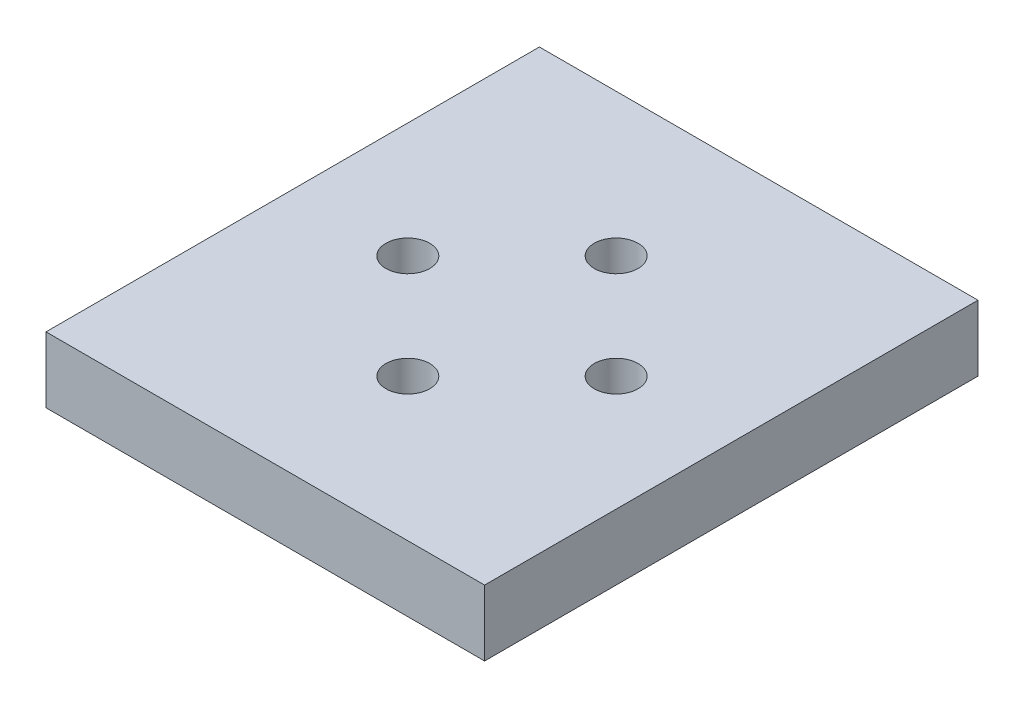
SolidWorks part; units mm, degrees
ref_plane "Front Plane" through (0, 0, 0) normal (0, 0, 1) x (1, 0, 0)
ref_plane "Top Plane" through (0, 0, 0) normal (0, 1, 0) x (1, 0, 0)
ref_plane "Right Plane" through (0, 0, 0) normal (1, 0, 0) x (0, 0, -1)
sketch "Sketch1" plane through (0, 0, 0) normal (0, 1, 0) x (1, 0, 0)
  line L1 (-20, 22.5) -> (20, 22.5)
  line L2 (-20, 22.5) -> (-20, -22.5)
  line L3 (-20, -22.5) -> (20, -22.5)
  line L4 (20, 22.5) -> (20, -22.5)
  line L5 (-20, 22.5) -> (20, -22.5) construction
  line L6 (-20, -22.5) -> (20, 22.5) construction
  point P0 (0, 0)
  dimension "D1" = 45
  dimension "D2" = 40
extrude "Boss-Extrude1" add sketch "Sketch1" along normal blind 6
sketch "Sketch2" plane through (0, 6, 0) normal (0, 1, 0) x (1, 0, 0)
  line L1 (-9.5, 9.5) -> (9.5, 9.5) construction
  line L2 (-9.5, 9.5) -> (-9.5, -9.5) construction
  line L3 (-9.5, -9.5) -> (9.5, -9.5) construction
  line L4 (9.5, 9.5) -> (9.5, -9.5) construction
  line L5 (-9.5, 9.5) -> (9.5, -9.5) construction
  line L6 (-9.5, -9.5) -> (9.5, 9.5) construction
  circle A0 centre (0, 9.5) radius 2
  circle A1 centre (9.5, 0) radius 2
  circle A2 centre (0, -9.5) radius 2
  circle A3 centre (-9.5, 0) radius 2
  point P0 (0, 0)
  dimension "D3" = 4
  dimension "D1" = 19
  dimension "D2" = 19
extrude "Cut-Extrude1" cut sketch "Sketch2" against normal blind 6
